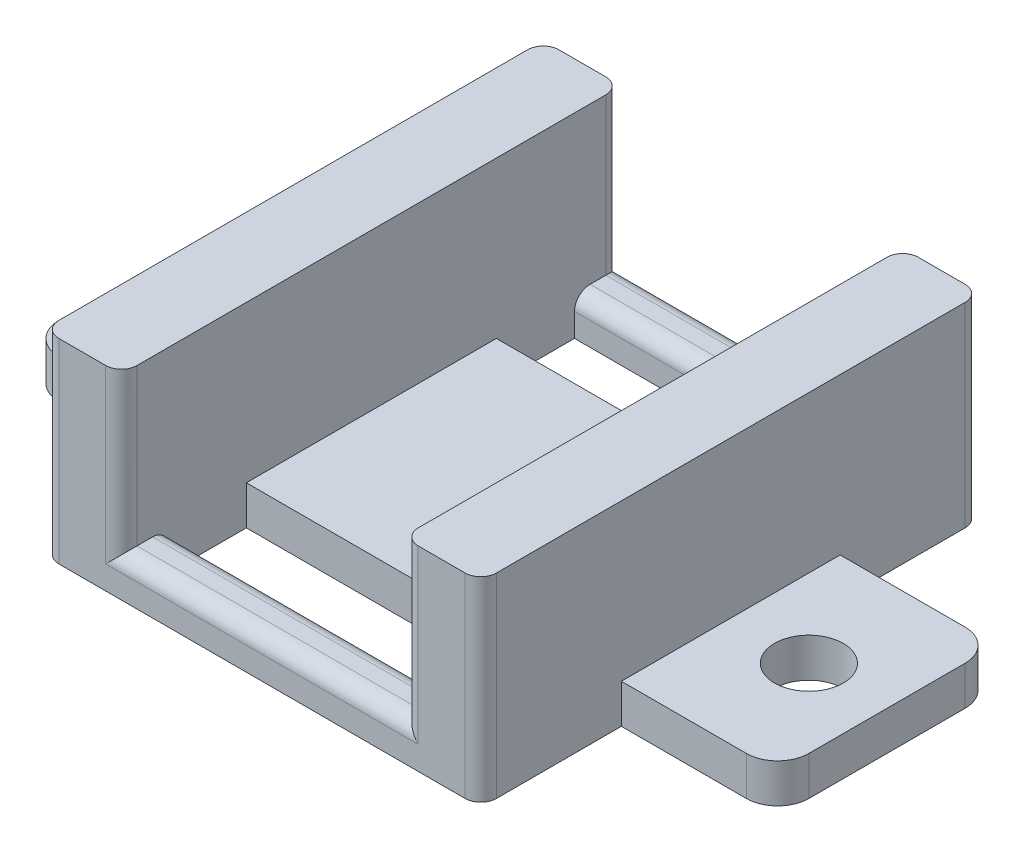
SolidWorks part; units mm, degrees
material "ABS"
ref_plane "Front Plane" through (0, 0, 0) normal (0, 0, 1) x (1, 0, 0)
ref_plane "Top Plane" through (0, 0, 0) normal (0, 1, 0) x (1, 0, 0)
ref_plane "Right Plane" through (0, 0, 0) normal (1, 0, 0) x (0, 0, -1)
sketch "Sketch1" plane through (0, 0, 0) normal (0, 1, 0) x (1, 0, 0)
  line L1 (0, 0) -> (28, 0)
  line L2 (0, 0) -> (0, 32)
  line L3 (0, 32) -> (28, 32)
  line L4 (28, 0) -> (28, 32)
  dimension "D1" = 32
  dimension "D2" = 28
extrude "Boss-Extrude1" add sketch "Sketch1" along normal blind 2.5
sketch "Sketch2" plane through (0, 2.5, 0) normal (0, 1, 0) x (1, 0, 0)
  line L0 (0, 0) -> (28, 0) construction
  line L1 (0, 32) -> (5, 32)
  line L2 (0, 32) -> (0, 0)
  line L3 (0, 0) -> (5, 0)
  line L4 (5, 30) -> (5, 0)
  line L5 (28, 32) -> (0, 32) construction
  line L6 (28, 0) -> (23, 0)
  line L7 (28, 0) -> (28, 32)
  line L8 (28, 32) -> (23, 32)
  line L9 (23, 0) -> (23, 30)
  line L12 (5, 32) -> (5, 30)
  line L14 (23, 32) -> (23, 30)
  line L16 (5, 0) -> (5, 4)
  line L18 (23, 0) -> (23, 4)
  line M13 (0, 32) -> (0, 0)
  line M14 (0, 0) -> (28, 0)
  line M15 (28, 0) -> (28, 32)
  line M16 (28, 32) -> (0, 32)
  dimension "D1" = 5
  dimension "D2" = 5
extrude "Boss-Extrude3" add sketch "Sketch2" along normal blind 10 contours L9 M14 M15 M16 | L4 M16 M13 M14
sketch "Sketch3" plane through (0, 2.5, 0) normal (0, 1, 0) x (1, 0, 0)
  line L0 (23, 32) -> (23, 0) construction
  line L1 (5, 32) -> (23, 32)
  line L2 (5, 32) -> (5, 24)
  line L3 (5, 24) -> (23, 24)
  line L4 (23, 32) -> (23, 24)
  line L6 (5, 0) -> (23, 0)
  line L7 (5, 0) -> (5, 8)
  line L8 (5, 8) -> (23, 8)
  line L9 (23, 0) -> (23, 8)
  dimension "D1" = 8
  dimension "D2" = 8
extrude "Cut-Extrude1" cut sketch "Sketch3" against normal blind 2.5
sketch "Sketch4" plane through (0, 0, 0) normal (0, -1, 0) x (1, 0, 0)
  line L0 (0, -9) -> (-10, -9)
  line L1 (0, -32) -> (0, 0) construction
  line L2 (-10, -9) -> (-10, -23)
  line L3 (-10, -23) -> (0, -23)
  line L4 (0, -9) -> (0, -23)
  line L5 (28, -32) -> (23, -32) construction
  line L6 (28, -9) -> (28, -23)
  line L7 (38, -9) -> (28, -9)
  line L8 (28, -23) -> (38, -23)
  line L9 (38, -9) -> (38, -23)
  circle A0 centre (-5, -16) radius 2.2
  circle A1 centre (33, -16) radius 2.2
  point P6 (-10, -16)
  point P7 (0, -16)
  dimension "D4" = 4.4
  dimension "D1" = 14
  dimension "D2" = 10
  dimension "D3" = 9
  dimension "D5" = 5
  dimension "D6" = 7
  dimension "D7" = 2
  dimension "D8" = 28
extrude "Boss-Extrude4" add sketch "Sketch4" against normal blind 2.5
fillet "Fillet1" radius 2 4 edges at (-10, 1.25, -9) (-10, 1.25, -23) (38, 1.25, -9) (38, 1.25, -23)
fillet "Fillet2" radius 1 8 edges at (23, 6.25, -32) (23, 6.25, 0) (5, 6.25, 0) (5, 6.25, -32) (0, 6.25, -32) (28, 6.25, -32) (28, 6.25, 0) (0, 6.25, 0)
sketch "Sketch5" plane through (0, 0, 0) normal (0, -1, 0) x (1, 0, 0)
  line L0 (1, 0) -> (4, 0) construction
  line L1 (2.5, 0) -> (26.7026, 0)
  line L2 (2.5, 0) -> (2.5, -3)
  line L3 (2.5, -3) -> (26.7026, -3)
  line L4 (26.7026, 0) -> (26.7026, -3)
  line L5 (4, -32) -> (1, -32) construction
  line L6 (2.5, -32) -> (25.7829, -32)
  line L7 (2.5, -32) -> (2.5, -29)
  line L8 (2.5, -29) -> (25.7829, -29)
  line L9 (25.7829, -32) -> (25.7829, -29)
  dimension "D1" = 3
  dimension "D2" = 3
extrude "Boss-Extrude5" add sketch "Sketch5" against normal blind 2.5
fillet "Fillet3" radius 1 4 edges at (14, 2.5, -3) (14, 2.5, 0) (14, 2.5, -32) (14, 2.5, -29)
